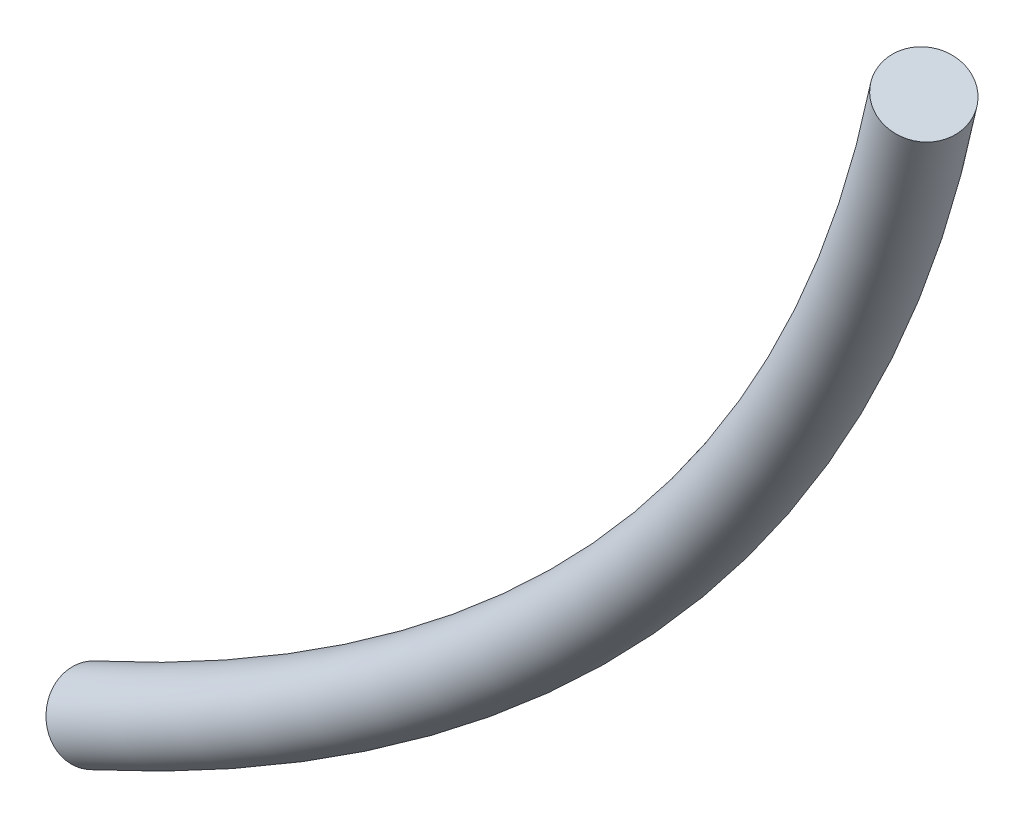
SolidWorks part; units mm, degrees
ref_plane "Front" through (0, 0, 0) normal (0, 0, 1) x (1, 0, 0)
ref_plane "Top" through (0, 0, 0) normal (0, 1, 0) x (1, 0, 0)
ref_plane "Right" through (0, 0, 0) normal (1, 0, 0) x (0, 0, -1)
ref_plane "Plane1" through (307.942, 3833.2012, -14920.0454) normal (-0.02, -0.2488, 0.9684) x (0.9998, -0.005, 0.0194)
sketch "Sketch2" plane through (307.942, 3833.2012, -14920.0454) normal (-0.02, -0.2488, 0.9684) x (0.9998, -0.005, 0.0194)
  line L0 (5194.0332, -8187.9627) -> (6077.2864, -7685.6681) construction
  line L1 (6769.7862, -6386.9201) -> (6907.5644, -6045.7776) construction
  arc A0 (5194.0332, -8187.9627) -> (6769.7862, -6386.9201) centre (3394.6008, -5023.7748) ccw
  dimension "D1" = 2438.4
  dimension "D2" = 2743.2
sketch "Sketch3" plane through (406.1781, 221.7469, 65.3537) normal (0.8691, 0.4745, 0.1398) x (0.1227, 0.067, -0.9902)
  circle A0 centre (17090.2256, -6254.7978) radius 50.8
sweep "Sweep1" add profiles "Sketch3" path "Sketch2"
